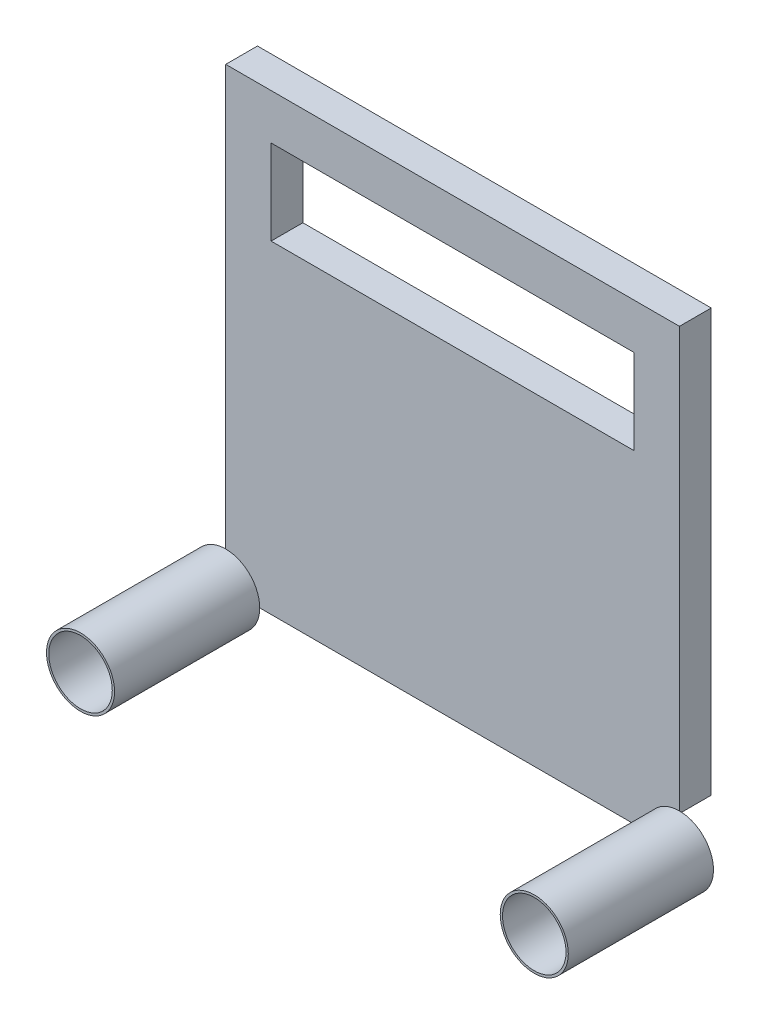
SolidWorks part; units mm, degrees
ref_plane "Front Plane" through (0, 0, 0) normal (0, 0, 1) x (1, 0, 0)
ref_plane "Top Plane" through (0, 0, 0) normal (0, 1, 0) x (1, 0, 0)
ref_plane "Right Plane" through (0, 0, 0) normal (1, 0, 0) x (0, 0, -1)
sketch "Sketch1" plane through (0, 0, 0) normal (0, 0, 1) x (1, 0, 0)
  line L1 (0, 0) -> (50, 0)
  line L2 (0, 0) -> (0, 50)
  line L3 (0, 50) -> (50, 50)
  line L4 (50, 0) -> (50, 50)
  dimension "D1" = 50
  dimension "D2" = 50
extrude "Boss-Extrude1" add sketch "Sketch1" along normal blind 3.5
sketch "Sketch2" plane through (0, 0, 3.5) normal (0, 0, 1) x (1, 0, 0)
  circle A0 centre (0, 0) radius 3.75
  circle A1 centre (50, 0) radius 3.75
  dimension "D1" = 7.5
  dimension "D2" = 7.5
extrude "Boss-Extrude2" add sketch "Sketch2" along normal blind 16
sketch "Sketch3" plane through (0, 0, 19.5) normal (0, 0, 1) x (1, 0, 0)
  circle A0 centre (0, 0) radius 3.5
  circle A1 centre (50, 0) radius 3.5
  dimension "D1" = 7
  dimension "D2" = 7
extrude "Cut-Extrude2" cut sketch "Sketch3" against normal blind 19.5
sketch "Sketch4" plane through (0, 0, 3.5) normal (0, 0, 1) x (1, 0, 0)
  line L0 (0, 50) -> (0, 3.75) construction
  line L1 (5, 35.6324) -> (45, 35.6324)
  line L2 (5, 35.6324) -> (5, 45)
  line L3 (5, 45) -> (45, 45)
  line L4 (45, 35.6324) -> (45, 45)
  line L5 (50, 3.75) -> (50, 50) construction
  line L6 (50, 50) -> (0, 50) construction
  dimension "D1" = 5
  dimension "D2" = 5
  dimension "D3" = 5
extrude "Cut-Extrude3" cut sketch "Sketch4" against normal blind 19.5
